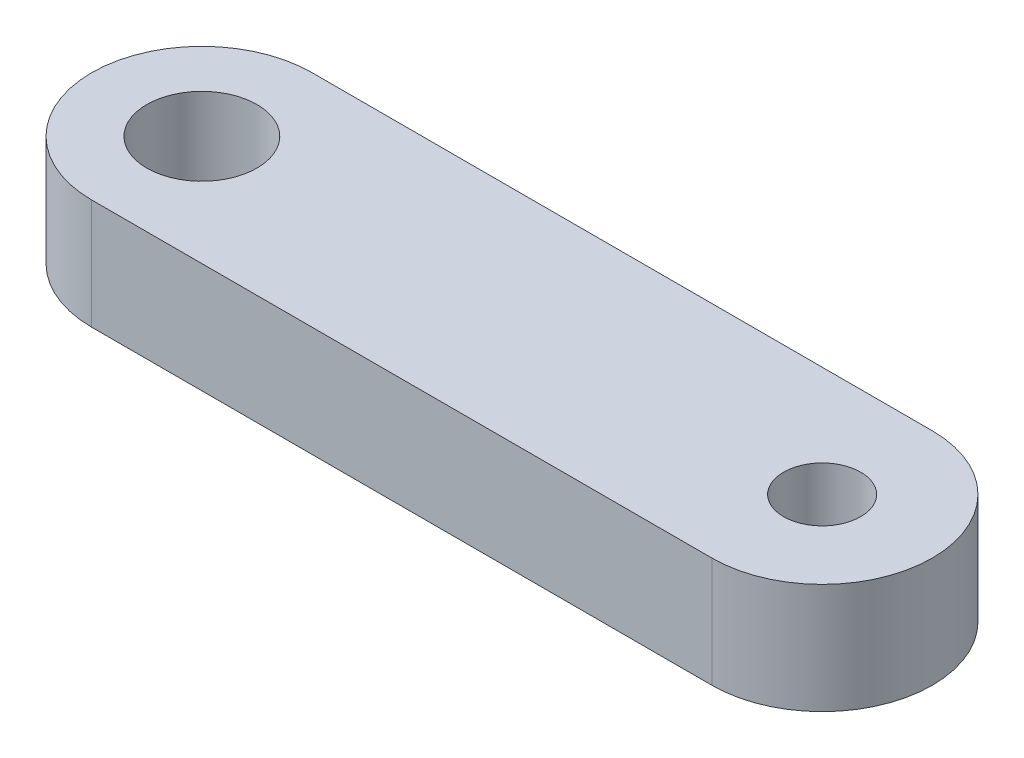
SolidWorks part; units mm, degrees
ref_plane "Płaszczyzna przednia" through (0, 0, 0) normal (0, 0, 1) x (1, 0, 0)
ref_plane "Płaszczyzna górna" through (0, 0, 0) normal (0, 1, 0) x (1, 0, 0)
ref_plane "Płaszczyzna prawa" through (0, 0, 0) normal (1, 0, 0) x (0, 0, -1)
sketch "Szkic1" plane through (0, 0, 0) normal (0, 1, 0) x (1, 0, 0)
  line L0 (-14.07, 0) -> (14.07, 0)
  line L1 (0, 0) -> (0, 10) construction
  line L2 (-14.07, 10) -> (14.07, 10)
  arc A0 (14.07, 10) -> (14.07, 0) centre (14.07, 5) cw
  arc A1 (-14.07, 10) -> (-14.07, 0) centre (-14.07, 5) ccw
  point P4 (0, 0)
  point P10 (0, 10)
  dimension "D1" = 28.14
  dimension "D2" = 10
  dimension "D3" = 28.14
extrude "Dodanie-wyciągnięcie2" add sketch "Szkic1" along normal blind 5 contours A1 L0 A0 L2
sketch "Szkic2" plane through (0, 5, 0) normal (0, 1, 0) x (1, 0, 0)
  line L0 (-14.07, 10) -> (-14.07, 0) construction
  line L1 (-14.07, 0) -> (14.07, 0) construction
  line L2 (14.07, 0) -> (14.07, 10) construction
  circle A0 centre (-14.07, 5) radius 2.5
  circle A1 centre (14.07, 5) radius 1.75
  dimension "D1" = 5
  dimension "D2" = 3.5
extrude "Wytnij-wyciągnięcie1" cut sketch "Szkic2" against normal blind 5
